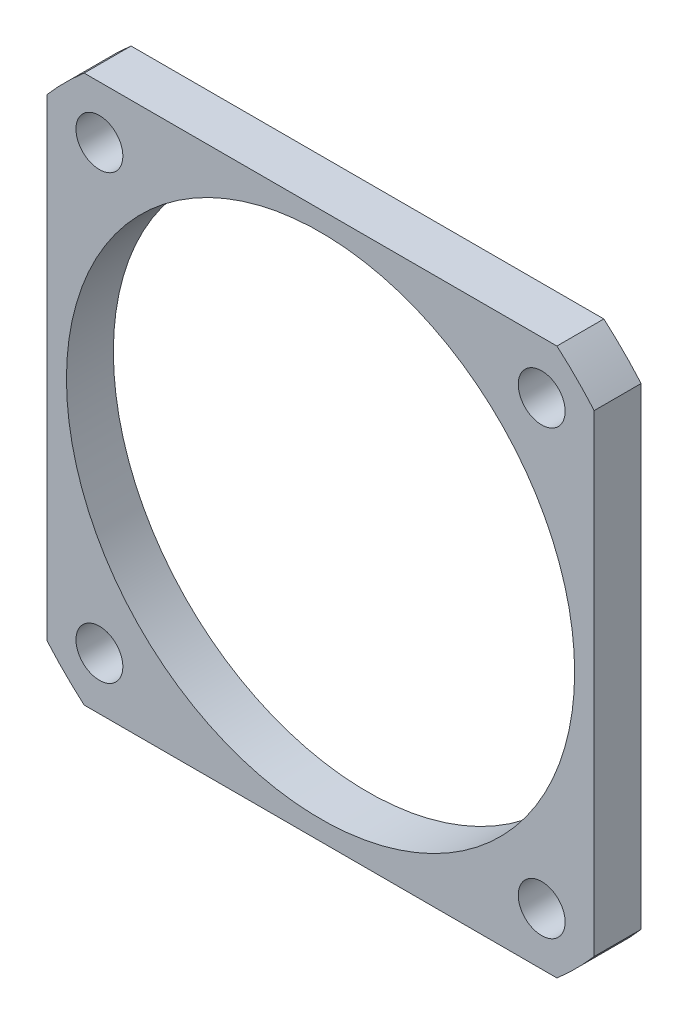
SolidWorks part; units mm, degrees
ref_plane "Front" through (0, 0, 0) normal (0, 0, 1) x (1, 0, 0)
ref_plane "Top" through (0, 0, 0) normal (0, 1, 0) x (1, 0, 0)
ref_plane "Right" through (0, 0, 0) normal (1, 0, 0) x (0, 0, -1)
sketch "Sketch1" plane through (0, 0, 0) normal (0, 0, 1) x (1, 0, 0)
  circle A0 centre (0, 0) radius 92.5
  dimension "D1" = 185
extrude "Boss-Extrude1" add sketch "Sketch1" along normal blind 12 separate body
sketch "Sketch2" plane through (0, 0, 12) normal (0, 0, 1) x (1, 0, 0)
  line L0 (0, 0) -> (0, 83.9481) construction
  line L1 (-70, 70) -> (70, 70)
  line L2 (-70, 70) -> (-70, -70)
  line L3 (-70, -70) -> (70, -70)
  line L4 (70, 70) -> (70, -70)
  line L5 (0, 0) -> (98.5359, 0) construction
  dimension "D1" = 140
  dimension "D2" = 140
extrude "Cut-Extrude1" cut sketch "Sketch2" against normal through all flip side to cut
sketch "Sketch3" plane through (0, 0, 12) normal (0, 0, 1) x (1, 0, 0)
  circle A0 centre (0, 0) radius 65
  dimension "D1" = 130
extrude "Cut-Extrude2" cut sketch "Sketch3" against normal through all
hole_wizard "Ø12.0 (12) Diameter Hole1" positions "Sketch5" profile "Sketch4" hole size "Ø12.0" standard "JIS" end condition through all
sketch "Sketch5" plane through (0, 0, 12) normal (0, 0, 1) x (1, 0, 0)
  line L0 (0, 0) -> (0, 88.9396) construction
  line L2 (0, 0) -> (56.5685, 56.5685) construction
  line L4 (0, 0) -> (87.1246, 0) construction
  circle A0 centre (0, 0) radius 80 construction
  point P0 (56.5685, 56.5685)
  point P15 (-56.5685, 56.5685)
  point P17 (-56.5685, -56.5685)
  point P19 (56.5685, -56.5685)
  dimension "D1" = 160
  dimension "D2" = 45
sketch "Sketch4" plane through (56.5685, 56.5685, 12) normal (1, 0, 0) x (0, -1, 0)
  line L0 (0, 0) -> (0, 12)
  line L1 (0, 12) -> (6, 12)
  line L2 (6, 12) -> (6, 0)
  line L5 (6, 0) -> (0, 0)
  line L11 (0, -6.35) -> (0, 107.95) construction
  dimension "Thru Hole Dia." = 12
  dimension "Thru Hole Depth" = 12
